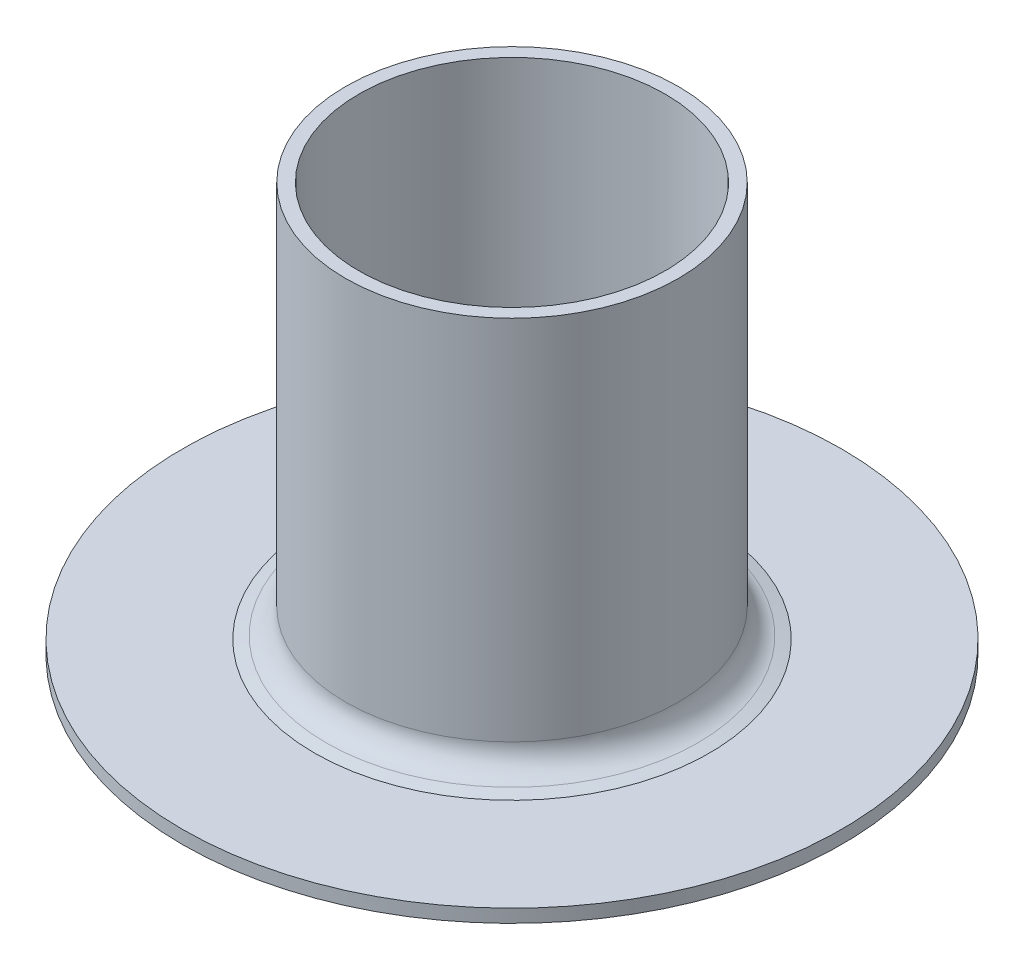
SolidWorks part; units mm, degrees
ref_plane "Front Plane" through (0, 0, 0) normal (0, 0, 1) x (1, 0, 0)
ref_plane "Top Plane" through (0, 0, 0) normal (0, 1, 0) x (1, 0, 0)
ref_plane "Right Plane" through (0, 0, 0) normal (1, 0, 0) x (0, 0, -1)
sketch "Sketch1" plane through (0, 0, 0) normal (0, 0, 1) x (1, 0, 0)
  line L1 (38.0492, 0) -> (35.82, 0.5973)
  line L2 (29.5148, -2.54) -> (29.5148, 76.2)
  line L3 (29.5148, 76.2) -> (32.0548, 76.2)
  line L4 (32.0548, 76.2) -> (32.0548, 5.5042)
  line L5 (0, 0) -> (0, 17.3811) construction
  line L6 (29.5148, -2.54) -> (63.5, -2.54)
  line L7 (63.5, -2.54) -> (63.5, 0)
  line L8 (63.5, 0) -> (38.0492, 0)
  arc A0 (32.0548, 5.5042) -> (35.82, 0.5973) centre (37.1348, 5.5042) ccw
  dimension "D2" = 5.08
  dimension "D1" = 2.54
  dimension "D3" = 32.0548
  dimension "D4" = 2.54
  dimension "D5" = 38.0492
  dimension "D6" = 76.2
  dimension "D7" = 15
  dimension "D8" = 63.5
revolve "Revolve1" add sketch "Sketch1" angle 360 about L5
